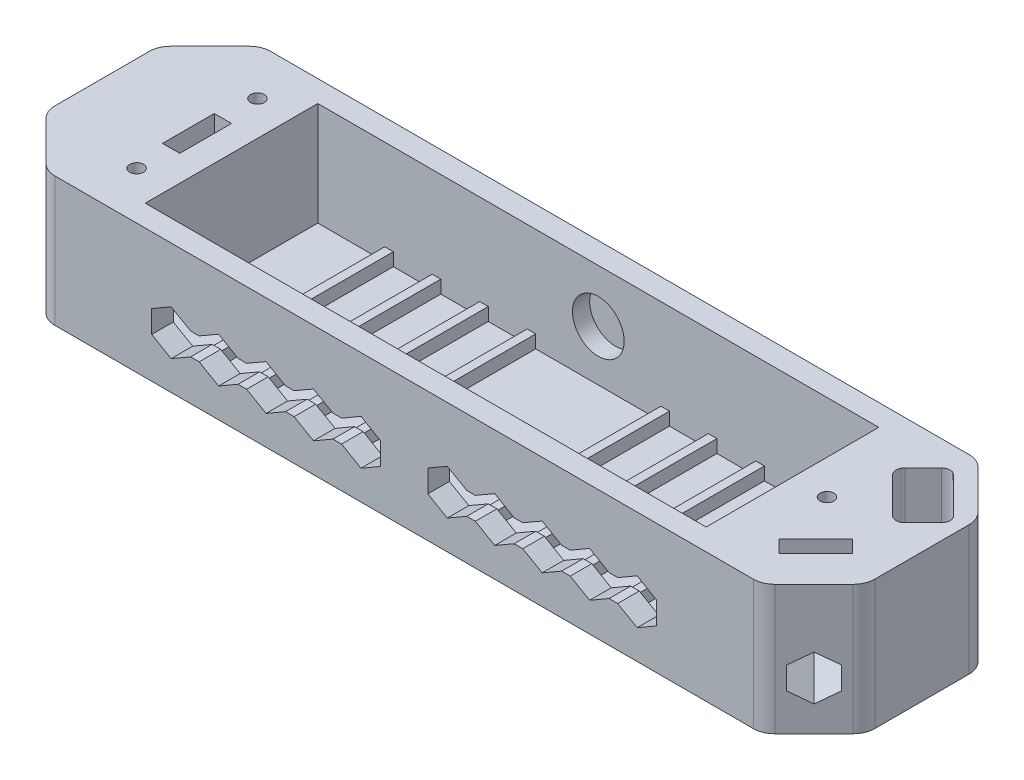
SolidWorks part; units mm, degrees
ref_plane "Front Plane" through (0, 0, 0) normal (0, 0, 1) x (1, 0, 0)
ref_plane "Top Plane" through (0, 0, 0) normal (0, 1, 0) x (1, 0, 0)
ref_plane "Right Plane" through (0, 0, 0) normal (1, 0, 0) x (0, 0, -1)
sketch "Sketch1" plane through (0, 0, 0) normal (0, 1, 0) x (1, 0, 0)
  line L0 (-47.5, -6.5) -> (-41.5, -12.5)
  line L1 (-41.5, 12.5) -> (41.5, 12.5)
  line L2 (-47.5, 6.5) -> (-47.5, -6.5)
  line L3 (-41.5, -12.5) -> (41.5, -12.5)
  line L4 (47.5, 6.5) -> (47.5, -6.5)
  line L5 (-47.5, 12.5) -> (47.5, -12.5) construction
  line L6 (-47.5, -12.5) -> (47.5, 12.5) construction
  line L7 (-47.5, 6.5) -> (-41.5, 12.5)
  line L8 (41.5, 12.5) -> (47.5, 6.5)
  line L9 (41.5, -12.5) -> (47.5, -6.5)
  point P0 (0, 0)
  dimension "D1" = 25
  dimension "D2" = 95
extrude "Boss-Extrude1" add sketch "Sketch1" along normal blind 15
sketch "Sketch3" plane through (0, 15, 0) normal (0, 1, 0) x (1, 0, 0)
  line L1 (-32.5, 10) -> (32.5, 10)
  line L2 (-32.5, 10) -> (-32.5, -10)
  line L3 (-32.5, -10) -> (32.5, -10)
  line L4 (32.5, 10) -> (32.5, -10)
  line L5 (-32.5, 10) -> (32.5, -10) construction
  line L6 (-32.5, -10) -> (32.5, 10) construction
  line L8 (47.5, -6.5) -> (47.5, 6.5) construction
  point P0 (0, 0)
  dimension "D1" = 20
  dimension "D2" = 15
extrude "Cut-Extrude2" cut sketch "Sketch3" against normal blind 12
sketch "Sketch4" plane through (0, 15, 0) normal (0, 1, 0) x (1, 0, 0)
  line L1 (-37.5, 3) -> (-35.5, 3)
  line L2 (-37.5, 3) -> (-37.5, -3)
  line L3 (-37.5, -3) -> (-35.5, -3)
  line L4 (-35.5, 3) -> (-35.5, -3)
  line L5 (-37.5, 3) -> (-35.5, -3) construction
  line L6 (-37.5, -3) -> (-35.5, 3) construction
  line L9 (-50, 0) -> (47.5, 0) construction
  line L16 (-32.5, 10) -> (-32.5, -10) construction
  line L18 (43.6071, -4.1645) -> (39.3645, -8.4071)
  line L23 (-47.5, 6.5) -> (-47.5, -6.5)
  line L24 (-47.5, -6.5) -> (-41.5, -12.5)
  line L25 (-41.5, -12.5) -> (41.5, -12.5)
  line L26 (41.5, -12.5) -> (47.5, -6.5)
  line L27 (47.5, -6.5) -> (47.5, 6.5)
  line L28 (47.5, 6.5) -> (41.5, 12.5)
  line L29 (41.5, 12.5) -> (-41.5, 12.5)
  line L30 (-41.5, 12.5) -> (-47.5, 6.5)
  line L31 (-47.5, 6.5) -> (-47.5, -6.5)
  line L32 (-47.5, -6.5) -> (-41.5, -12.5)
  line L33 (-41.5, -12.5) -> (41.5, -12.5)
  line L34 (41.5, -12.5) -> (47.5, -6.5)
  line L35 (47.5, -6.5) -> (47.5, 6.5)
  line L36 (47.5, 6.5) -> (41.5, 12.5)
  line L37 (41.5, 12.5) -> (-41.5, 12.5)
  line L38 (-41.5, 12.5) -> (-47.5, 6.5)
  line L42 (41.6109, 9.5607) -> (45.6967, 5.4749)
  line L43 (43.6071, -4.1645) -> (42.1929, -2.7503)
  line L44 (39.3645, -8.4071) -> (37.9503, -6.9929)
  line L45 (42.1929, -2.7503) -> (37.9503, -6.9929)
  line L46 (40.1967, 9.5607) -> (38.0754, 7.4393)
  line L47 (45.6967, 4.0607) -> (43.5754, 1.9393)
  line L48 (38.0754, 6.0251) -> (42.1612, 1.9393)
  arc A0 (43.5754, 1.9393) -> (42.1612, 1.9393) centre (42.8683, 2.6464) cw
  arc A1 (45.6967, 5.4749) -> (45.6967, 4.0607) centre (44.9896, 4.7678) cw
  arc A2 (40.1967, 9.5607) -> (41.6109, 9.5607) centre (40.9038, 8.8536) cw
  arc A3 (38.0754, 7.4393) -> (38.0754, 6.0251) centre (38.7825, 6.7322) ccw
  point P0 (-36.5, 0)
  point P5 (39.136, 8.5)
  point P8 (44.636, 3)
  point P15 (42.8683, 1.2322)
  point P29 (46.4038, 4.7678)
  point P37 (42.9, -3.4574)
  point P38 (38.6574, -7.7)
  dimension "D6" = 2
  dimension "D8" = 5
  dimension "D11" = 1
  dimension "D2" = 2
  dimension "D3" = 6
  dimension "D4" = 3
  dimension "D5" = 6
  dimension "D7" = 2
  dimension "D9" = 4
  dimension "D10" = 3
  dimension "D12" = 4.6
  dimension "D13" = 4.8
  dimension "D1" = 0
extrude "Cut-Extrude4" cut sketch "Sketch4" against normal through all contours A2 L42 A1 L47 A0 L48 A3 L46
sketch "Sketch5" plane through (27, 0, 27) normal (0.7071, 0, 0.7071) x (0.7071, 0, -0.7071)
  line L1 (24.7487, 8.2) -> (22.4971, 6.9)
  line L2 (22.4971, 6.9) -> (22.4971, 4.3)
  line L3 (22.4971, 4.3) -> (24.7487, 3)
  line L4 (24.7487, 3) -> (27.0004, 4.3)
  line L5 (27.0004, 4.3) -> (27.0004, 6.9)
  line L6 (27.0004, 6.9) -> (24.7487, 8.2)
  line L8 (24.7487, 15) -> (24.7487, 0) construction
  line L9 (20.5061, 15) -> (28.9914, 15) construction
  line L10 (20.5061, 0) -> (28.9914, 0) construction
  circle A0 centre (24.7487, 5.6) radius 2.2517 construction
  dimension "D1" = 2.6
  dimension "D2" = 3
hole_wizard "M2 Tapped Hole1" positions "3DSketch5" profile "Sketch14" tap size "M2" standard "ISO"
sketch3d "3DSketch5"
  line L0 (-50, 15, 0) -> (47.5, 15, 0) construction
  line L1 (32.5, 15, 10) -> (32.5, 15, -10) construction
  line L2 (-37.5, 15, -3) -> (-35.5, 15, -3) construction
  line L3 (-32.5, 15, -10) -> (-32.5, 15, 10) construction
  line L4 (-37.5, 15, 3) -> (-35.5, 15, 3) construction
  point P0 (-36.5, 15, 7)
  point P2 (-36.5, 15, -7)
  point P5 (36.5, 15, 0)
  dimension "D1" = 4
  dimension "D2" = 4
  dimension "D3" = 4
  dimension "D4" = 4
  dimension "D5" = 4
sketch "Sketch14" plane through (-36.5, 15, 7) normal (1, 0, 0) x (0, 0, 1)
  line L0 (0, 0) -> (0, 5)
  line L1 (0, 5) -> (0.8, 4.5193)
  line L2 (0.8, 4.5193) -> (0.8, 0)
  line L5 (0.8, 0) -> (0, 0)
  line L10 (0, 5) -> (-0.8, 4.5193) construction
  line L11 (0, -6.35) -> (0, 107.95) construction
  dimension "Tap Drill Dia." = 1.6
  dimension "Tap Drill Depth" = 5
  dimension "Drill Angle" = 118
cosmetic thread "Hole Thread1" parameters "D1"=4, "D2"=2
cosmetic thread "Hole Thread2" parameters "D1"=4, "D2"=2
cosmetic thread "Hole Thread3" parameters "D1"=4, "D2"=2
fillet "Fillet4" radius 2.5 8 edges at (41.5, 7.5, -12.5) (47.5, 7.5, -6.5) (-41.5, 7.5, -12.5) (-47.5, 7.5, -6.5) (-47.5, 7.5, 6.5) (47.5, 7.5, 6.5) (41.5, 7.5, 12.5) (-41.5, 7.5, 12.5)
sketch "Sketch15" plane through (0, 0, -10) normal (0, 0, 1) x (1, 0, 0)
  line L0 (0, 2.7691) -> (0, 15) construction
  line L1 (32.5, 15) -> (-32.5, 15) construction
  circle A0 centre (0, 8.8846) radius 3
  point P5 (0, 8.8846)
  dimension "D1" = 6
extrude "Cut-Extrude10" cut sketch "Sketch15" against normal blind 2
sketch "Sketch16" plane through (-47.5, 0, 0) normal (-1, 0, 0) x (0, 0, 1)
  line L0 (-5.4645, 7.5) -> (5.4645, 7.5) construction
  line L1 (0, 10.1) -> (-2.2517, 8.8)
  line L2 (-2.2517, 8.8) -> (-2.2517, 6.2)
  line L3 (-2.2517, 6.2) -> (0, 4.9)
  line L4 (5.4645, 15) -> (-5.4645, 15)
  line L5 (-5.4645, 15) -> (-5.4645, 0)
  line L6 (-5.4645, 0) -> (5.4645, 0)
  line L7 (5.4645, 0) -> (5.4645, 15)
  line L8 (5.4645, 15) -> (-5.4645, 15)
  line L9 (-5.4645, 15) -> (-5.4645, 0)
  line L10 (-5.4645, 0) -> (5.4645, 0)
  line L11 (5.4645, 0) -> (5.4645, 15)
  line L12 (0, 4.9) -> (2.2517, 6.2)
  line L13 (2.2517, 6.2) -> (2.2517, 8.8)
  line L14 (2.2517, 8.8) -> (0, 10.1)
  line L15 (0, 0) -> (0, 15) construction
  circle A0 centre (0, 7.5) radius 2.2517 construction
  dimension "D2" = 2.6
  dimension "D1" = 0
extrude "Cut-Extrude11" cut sketch "Sketch16" against normal blind 8 contours L1 L2 L3 L12 L13 L14
extrude "Cut-Extrude12" cut sketch "Sketch5" against normal blind 10
sketch "Sketch17" plane through (0, 0, 12.5) normal (0, 0, 1) x (1, 0, 0)
  line L0 (-40.4645, 7.5) -> (40.4645, 7.5) construction
  line L1 (-40.4645, 15) -> (-40.4645, 0) construction
  line L2 (-40.4645, 0) -> (40.4645, 0) construction
  line L3 (40.4645, 0) -> (40.4645, 15) construction
  line L4 (0, 15) -> (0, 0) construction
  line L5 (-40.4645, 15) -> (40.4645, 15) construction
  line L6 (7.2517, 7.3) -> (8.2517, 7.3)
  line L7 (7.2517, 4.7) -> (7.2517, 7.3) construction
  line L8 (7.2517, 7.3) -> (5, 8.6)
  line L9 (5, 8.6) -> (2.7483, 7.3)
  line L10 (2.7483, 7.3) -> (2.7483, 4.7)
  line L11 (2.7483, 4.7) -> (5, 3.4)
  line L12 (5, 3.4) -> (7.2517, 4.7)
  line L13 (7.2517, 4.7) -> (8.2517, 4.7)
  line L14 (12.7517, 4.7) -> (12.7517, 7.3) construction
  line L15 (12.7517, 7.3) -> (10.5, 8.6)
  line L16 (10.5, 8.6) -> (8.2483, 7.3)
  line L17 (8.2483, 7.3) -> (8.2483, 4.7) construction
  line L18 (8.2483, 4.7) -> (10.5, 3.4)
  line L19 (10.5, 3.4) -> (12.7517, 4.7)
  line L20 (12.7517, 7.3) -> (13.7517, 7.3)
  line L21 (12.7517, 4.7) -> (13.7517, 4.7)
  line L22 (18.2517, 4.7) -> (18.2517, 7.3) construction
  line L23 (18.2517, 7.3) -> (16, 8.6)
  line L24 (16, 8.6) -> (13.7483, 7.3)
  line L25 (13.7483, 7.3) -> (13.7483, 4.7) construction
  line L26 (13.7483, 4.7) -> (16, 3.4)
  line L27 (16, 3.4) -> (18.2517, 4.7)
  line L28 (18.2517, 7.3) -> (19.2517, 7.3)
  line L29 (18.2517, 4.7) -> (19.2517, 4.7)
  line L30 (23.7517, 4.7) -> (23.7517, 7.3) construction
  line L31 (23.7517, 7.3) -> (21.5, 8.6)
  line L32 (21.5, 8.6) -> (19.2483, 7.3)
  line L33 (19.2483, 7.3) -> (19.2483, 4.7) construction
  line L34 (19.2483, 4.7) -> (21.5, 3.4)
  line L35 (21.5, 3.4) -> (23.7517, 4.7)
  line L36 (23.7517, 7.3) -> (24.7517, 7.3)
  line L37 (23.7517, 4.7) -> (24.7517, 4.7)
  line L38 (29.2517, 4.7) -> (29.2517, 7.3)
  line L39 (29.2517, 7.3) -> (27, 8.6)
  line L40 (27, 8.6) -> (24.7483, 7.3)
  line L41 (24.7483, 7.3) -> (24.7483, 4.7) construction
  line L42 (24.7483, 4.7) -> (27, 3.4)
  line L43 (27, 3.4) -> (29.2517, 4.7)
  line L48 (40.4645, 15) -> (-40.4645, 15)
  line L49 (-40.4645, 15) -> (-40.4645, 0)
  line L50 (-40.4645, 0) -> (40.4645, 0)
  line L51 (40.4645, 0) -> (40.4645, 15)
  line L52 (40.4645, 15) -> (-40.4645, 15)
  line L53 (-40.4645, 15) -> (-40.4645, 0)
  line L54 (34.7517, 7.3) -> (35.7517, 7.3) [skipped]
  line L55 (34.7517, 4.7) -> (35.7517, 4.7) [skipped]
  line L56 (29.2517, 4.7) -> (30.2517, 4.7) [skipped]
  line L57 (34.7517, 4.7) -> (34.7517, 7.3) [skipped]
  line L58 (30.2483, 4.7) -> (32.5, 3.4) [skipped]
  line L59 (32.5, 3.4) -> (34.7517, 4.7) [skipped]
  line L60 (30.2483, 7.3) -> (30.2483, 4.7) construction
  line L61 (34.7517, 7.3) -> (32.5, 8.6) [skipped]
  line L62 (32.5, 8.6) -> (30.2483, 7.3) [skipped]
  line L63 (29.2517, 7.3) -> (30.2517, 7.3) [skipped]
  line L64 (-40.4645, 0) -> (40.4645, 0)
  line L65 (40.4645, 0) -> (40.4645, 15)
  circle A0 centre (5, 6) radius 2.2517 construction
  dimension "D1" = 2.6
  dimension "D2" = 1
  dimension "D3" = 6
  dimension "D4" = 5
  dimension "D5" = 6
  dimension "D6" = 5.5
  dimension "D7" = 0
extrude "Cut-Extrude13" cut sketch "Sketch17" against normal blind 10
mirror "Mirror1" about plane through (0, 0, 0) normal (1, 0, 0) of "Cut-Extrude13"
sketch "Sketch19" plane through (0, 0, 10) normal (0, 0, -1) x (-1, 0, 0)
  line L0 (-24.7483, 3) -> (-24.7483, 4.5)
  line L1 (-24.7483, 4.5) -> (-23.7517, 4.5)
  line L2 (-23.7517, 4.5) -> (-23.7517, 3)
  line L4 (32.5, 15) -> (-32.5, 15)
  line L5 (-32.5, 15) -> (-32.5, 3)
  line L6 (-32.5, 3) -> (32.5, 3)
  line L7 (32.5, 3) -> (32.5, 15)
  line L8 (32.5, 15) -> (-32.5, 15)
  line L9 (-32.5, 15) -> (-32.5, 3)
  line L10 (-32.5, 3) -> (32.5, 3)
  line L11 (32.5, 3) -> (32.5, 15)
  dimension "D2" = 1.5
  dimension "D3" = 0.9967
  dimension "D1" = 0
extrude "Boss-Extrude2" add sketch "Sketch19" along normal blind 20
pattern_linear "LPattern1" count 4 spacing 5.5 along (-1, 0, 0) of "Boss-Extrude2"
mirror "Mirror2" about plane through (0, 0, 0) normal (1, 0, 0) of "LPattern1", "Boss-Extrude2"
sketch "Sketch20" plane through (0, 15, 0) normal (0, 1, 0) x (1, 0, 0)
  line L0 (39.3645, -8.4071) -> (37.9503, -6.9929) construction
  line L1 (42.1929, -2.7503) -> (37.9503, -6.9929) construction
  line L2 (43.6071, -4.1645) -> (42.1929, -2.7503) construction
  line L3 (43.6071, -4.1645) -> (39.3645, -8.4071) construction
  line L4 (-35.5, 3) -> (-35.5, -3) construction
  line L5 (-37.5, 3) -> (-35.5, 3) construction
  line L6 (-37.5, 3) -> (-37.5, -3) construction
  line L7 (-37.5, -3) -> (-35.5, -3) construction
  line L8 (39.3645, -8.4071) -> (37.9503, -6.9929)
  line L9 (42.1929, -2.7503) -> (37.9503, -6.9929)
  line L10 (43.6071, -4.1645) -> (42.1929, -2.7503)
  line L11 (43.6071, -4.1645) -> (39.3645, -8.4071)
  line L12 (-35.5, 3) -> (-35.5, -3)
  line L13 (-37.5, 3) -> (-35.5, 3)
  line L14 (-37.5, 3) -> (-37.5, -3)
  line L15 (-37.5, -3) -> (-35.5, -3)
extrude "Cut-Extrude14" cut sketch "Sketch20" against normal blind 6.5
